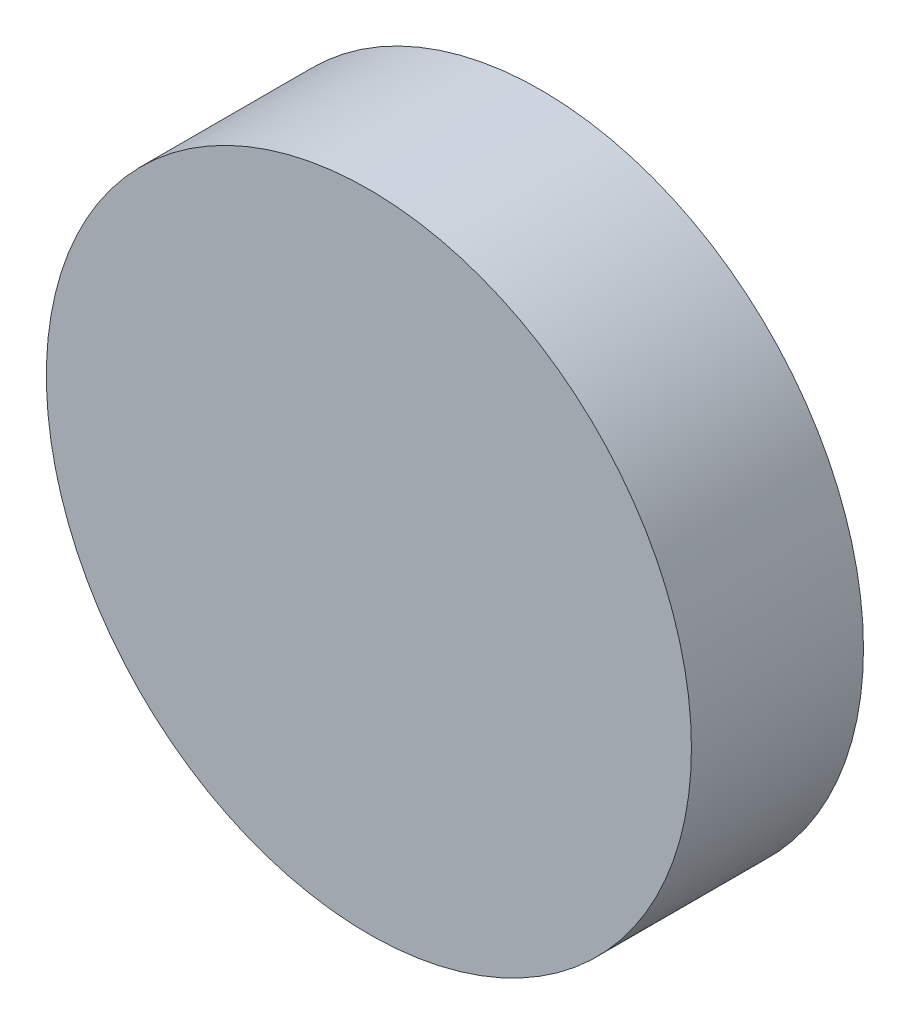
SolidWorks part; units mm, degrees
ref_plane "Front Plane" through (0, 0, 0) normal (0, 0, 1) x (1, 0, 0)
ref_plane "Top Plane" through (0, 0, 0) normal (0, 1, 0) x (1, 0, 0)
ref_plane "Right Plane" through (0, 0, 0) normal (1, 0, 0) x (0, 0, -1)
sketch "Sketch1" plane through (0, 0, 0) normal (0, 0, 1) x (1, 0, 0)
  circle A0 centre (0, 0) radius 7.5
  dimension "D1" = 15
extrude "Boss-Extrude1" add sketch "Sketch1" along normal blind 4
sketch "Sketch2" plane through (0, 0, 4) normal (0, 0, 1) x (1, 0, 0)
  line L0 (-7.5, 0) -> (7.5, 0) construction
  line L1 (0, 7.5) -> (0, -7.5) construction
  circle A0 centre (0, 0) radius 7.5 construction
  point P7 (0, 0)
